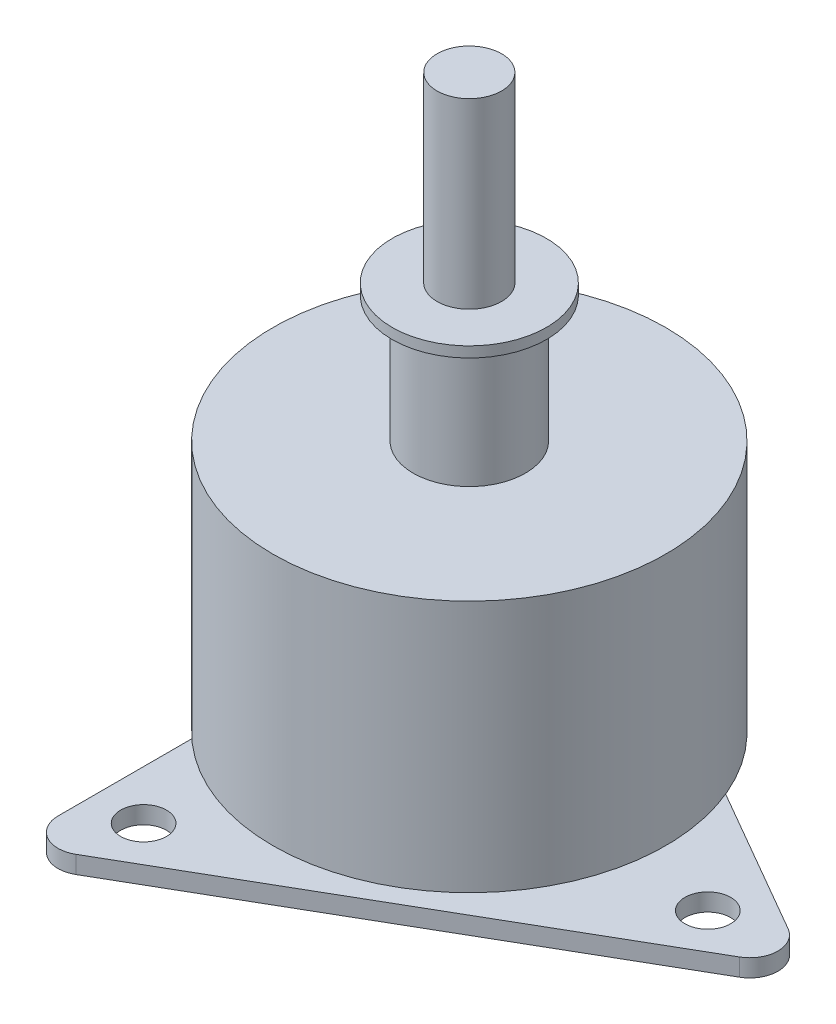
SolidWorks part; units mm, degrees
ref_plane "Front Plane" through (0, 0, 0) normal (0, 0, 1) x (1, 0, 0)
ref_plane "Top Plane" through (0, 0, 0) normal (0, 1, 0) x (1, 0, 0)
ref_plane "Right Plane" through (0, 0, 0) normal (1, 0, 0) x (0, 0, -1)
sketch "Sketch1" plane through (0, 0, 0) normal (0, 1, 0) x (1, 0, 0)
  line L0 (-23.6476, 0) -> (38.4012, 0) construction
  line L1 (17, 0) -> (-8.5, 14.7224) construction
  line L2 (-8.5, 14.7224) -> (-8.5, -14.7224) construction
  line L3 (-8.5, -14.7224) -> (17, 0) construction
  line L4 (24, 0) -> (-12, 20.7846)
  line L5 (-12, 20.7846) -> (-12, -20.7846)
  line L6 (-12, -20.7846) -> (24, 0)
  circle A0 centre (0, 0) radius 17 construction
  dimension "D1" = 34
  dimension "D2" = 3.5
extrude "Boss-Extrude1" add sketch "Sketch1" along normal blind 1.25
hole_wizard "#4 Clearance Hole1" positions "Sketch3" profile "Sketch2" hole size "#4" standard "ANSI Inch"
sketch "Sketch3" plane through (0, 1.25, 0) normal (0, 1, 0) x (1, 0, 0)
  line L0 (-18.8433, 0) -> (35.4351, 0) construction
  line L1 (0, 0) -> (-12, 20.7846) construction
  line L3 (0, 0) -> (-12, -20.7846) construction
  line L5 (0, 0) -> (24, 0) construction
  circle A0 centre (0, 0) radius 17 construction
  point P0 (-8.5, 14.7224)
  point P2 (-8.5, -14.7224)
  point P4 (17, 0)
  dimension "D1" = 34
sketch "Sketch2" plane through (-8.5, 1.25, -14.7224) normal (1, 0, 0) x (0, 0, 1)
  line L0 (0, 0) -> (0, 2.2296)
  line L1 (0, 2.2296) -> (1.6319, 1.249)
  line L2 (1.6319, 1.249) -> (1.6319, 0)
  line L5 (1.6319, 0) -> (0, 0)
  line L10 (0, 2.2296) -> (-1.632, 1.249) construction
  line L11 (0, -6.35) -> (0, 107.95) construction
  dimension "Hole Dia." = 3.2639
  dimension "Hole Depth" = 1.249
  dimension "Drill Angle" = 118
sketch "Sketch4" plane through (0, 0, 0) normal (1, 0, 0) x (0, 0, -1)
  line L0 (0, 1.25) -> (6, 1.25)
  line L1 (0, 1.25) -> (20.7846, 1.25) construction
  line L2 (6, 1.25) -> (6, 3.75)
  line L3 (6, 3.75) -> (14, 3.75)
  line L4 (14, 3.75) -> (14, 21.75)
  line L5 (14, 21.75) -> (4, 21.75)
  line L6 (4, 21.75) -> (4, 30.75)
  line L7 (4, 30.75) -> (5.5, 30.75)
  line L8 (5.5, 30.75) -> (5.5, 31.5)
  line L9 (5.5, 31.5) -> (2.3, 31.5)
  line L10 (2.3, 31.5) -> (2.3, 44.5)
  line L11 (2.3, 44.5) -> (0, 44.5)
  line L12 (0, 44.5) -> (0, 1.25)
  line L13 (-20.7846, 0) -> (0, 0) construction
  dimension "D1" = 6
  dimension "D2" = 31.5
  dimension "D3" = 2.5
  dimension "D4" = 18
  dimension "D5" = 14
  dimension "D6" = 9
  dimension "D7" = 5.5
  dimension "D8" = 2.3
  dimension "D9" = 4
  dimension "D10" = 13
revolve "Revolve1" add sketch "Sketch4" angle 360 about L12
sketch "Sketch5" plane through (0, 0, 0) normal (0, -1, 0) x (1, 0, 0)
  circle A0 centre (0, 0) radius 7.5
  dimension "D1" = 15
extrude "Boss-Extrude2" add sketch "Sketch5" along normal blind 3.25
fillet "Fillet2" radius 2 3 edges at (-12, 0.625, 20.7846) (-12, 0.625, -20.7846) (24, 0.625, 0)
